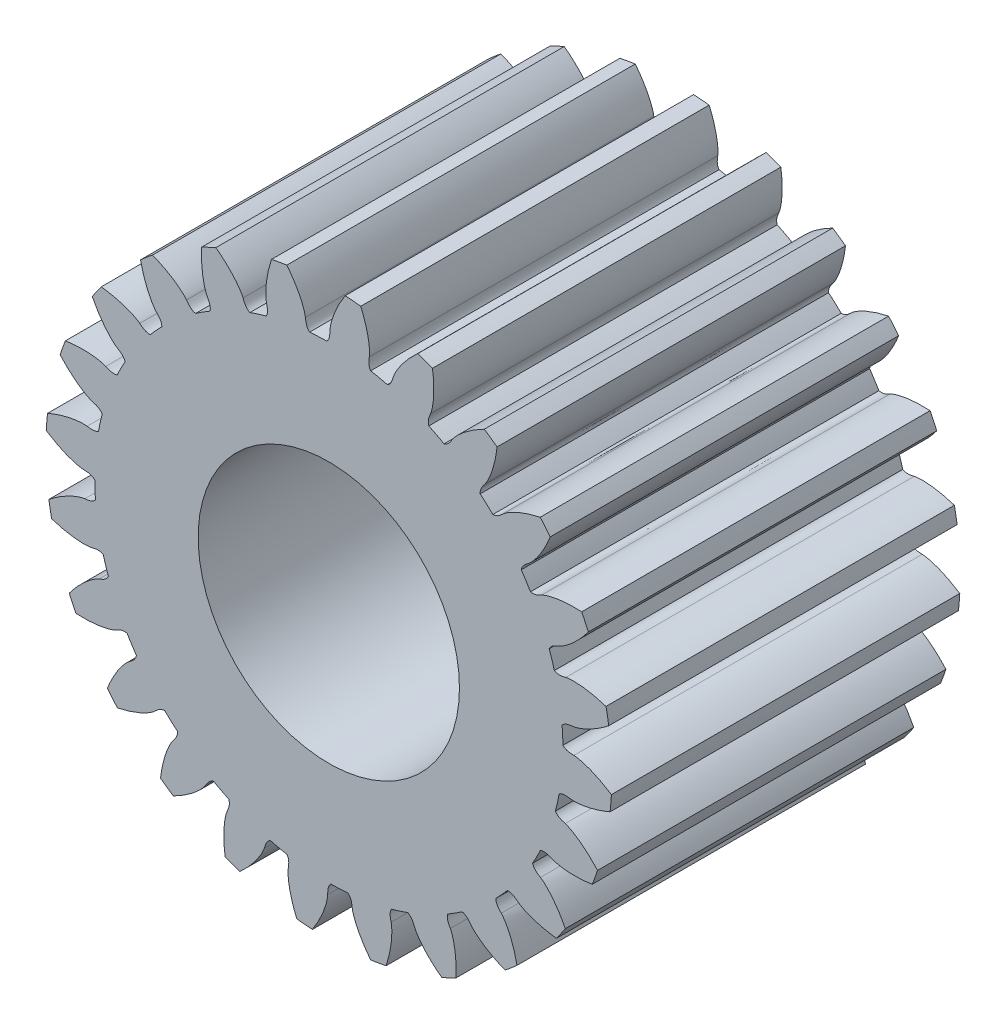
SolidWorks part; units mm, degrees
ref_plane "前视基准面" through (0, 0, 0) normal (0, 0, 1) x (1, 0, 0)
ref_plane "上视基准面" through (0, 0, 0) normal (0, 1, 0) x (1, 0, 0)
ref_plane "右视基准面" through (0, 0, 0) normal (1, 0, 0) x (0, 0, -1)
other "Configuration Table"
sketch "草图1" plane through (0, 0, 0) normal (0, 0, 1) x (1, 0, 0)
  line L0 (0, 0) -> (0.12, 5.9988) construction
  line L1 (0, 0) -> (0.5548, 6.4763) construction
  line L2 (0, 0) -> (1.3953, 6.3485) construction
  circle A0 centre (0, 0) radius 5.375
  circle A2 centre (0, 0) radius 6.5
  circle A3 centre (0, 0) radius 6
  spline S0 degree 4 poles (0.0267, 5.6277) (0.0268, 5.6323) (0.0274, 5.6451) (0.0298, 5.6692) (0.0354, 5.7085) (0.0451, 5.7581) (0.0606, 5.8218) (0.0826, 5.8959) (0.1105, 5.9764) (0.1451, 6.0628) (0.1832, 6.1477) (0.2244, 6.2312) (0.2685, 6.3131) (0.3253, 6.4109) (0.398, 6.5258) (0.4898, 6.6567) (0.6016, 6.8007) (0.7236, 6.9423) (0.85, 7.0774) (0.9849, 7.2085) (1.1204, 7.3315) (1.268, 7.4534) (1.4077, 7.5629) (1.5714, 7.6786) (1.7056, 7.77) (1.8898, 7.8829) (2.0007, 7.9473) (2.1328, 8.0198) (2.1927, 8.0506) (2.2296, 8.0696) knots 0 0 0 0 0 0.005377 0.015084 0.028532 0.04661 0.064855 0.092111 0.119476 0.146842 0.174209 0.201575 0.228941 0.256307 0.307035 0.361767 0.4165 0.471232 0.525964 0.580697 0.635429 0.690161 0.744894 0.799626 0.854358 0.909091 0.954545 1 1 1 1 1 construction
  spline S1 degree 4 poles (0.0267, 5.6277) (0.0268, 5.6323) (0.0274, 5.6451) (0.0298, 5.6692) (0.0354, 5.7085) (0.0451, 5.7581) (0.0606, 5.8218) (0.0826, 5.8959) (0.1105, 5.9764) (0.1451, 6.0628) (0.1832, 6.1477) (0.2244, 6.2312) (0.2685, 6.3131) (0.3119, 6.3879) (0.3451, 6.4416) (0.3666, 6.4752) (0.3757, 6.4891) knots 0 0 0 0 0 0.005377 0.015084 0.028532 0.04661 0.064855 0.092111 0.119476 0.146842 0.174209 0.201575 0.228941 0.256307 0.275859 0.275859 0.275859 0.275859 0.275859
  spline S2 degree 3 poles (0.0267, 5.6277) (0.0247, 5.5363) (0.0211, 5.4458) (-0.0474, 5.3748) knots 0 0 0 0 1 1 1 1
  spline S3 degree 3 poles (0.9308, 5.5502) (0.9172, 5.4599) (0.9054, 5.37) (0.9608, 5.2884) knots 0 0 0 0 1 1 1 1
  spline S4 degree 4 poles (0.9308, 5.5502) (0.9314, 5.5548) (0.933, 5.5675) (0.9348, 5.5917) (0.9359, 5.6313) (0.9348, 5.6819) (0.9304, 5.7473) (0.9214, 5.8241) (0.9075, 5.9082) (0.8881, 5.9991) (0.8651, 6.0893) (0.8386, 6.1786) (0.8091, 6.2668) (0.779, 6.3479) (0.7555, 6.4065) (0.74, 6.4432) (0.7334, 6.4585) knots 0 0 0 0 0 0.005377 0.015084 0.028532 0.04661 0.064855 0.092111 0.119476 0.146842 0.174209 0.201575 0.228941 0.256307 0.275859 0.275859 0.275859 0.275859 0.275859
  spline S5 degree 4 poles (1.4824, 5.429) (1.4837, 5.4334) (1.4876, 5.4456) (1.4961, 5.4683) (1.5117, 5.5048) (1.5339, 5.5502) (1.5653, 5.6077) (1.6057, 5.6737) (1.6536, 5.7442) (1.7093, 5.8187) (1.7681, 5.8908) (1.8295, 5.9608) (1.8933, 6.0285) (1.9546, 6.0895) (2.0005, 6.1328) (2.03, 6.1597) (2.0424, 6.1708) knots 0 0 0 0 0 0.005377 0.015084 0.028532 0.04661 0.064855 0.092111 0.119476 0.146842 0.174209 0.201575 0.228941 0.256307 0.275859 0.275859 0.275859 0.275859 0.275859
  spline S6 degree 3 poles (1.4824, 5.429) (1.4568, 5.3413) (1.4299, 5.2548) (1.3453, 5.2039) knots 0 0 0 0 1 1 1 1
  dimension "D1" = 12
  dimension "D2" = 13
  dimension "D3" = 10.75
  dimension "D5" = 3.75
  dimension "D6" = 11.25
sketch "草图3" plane through (0, 0, 0) normal (0, 0, 1) x (1, 0, 0)
  circle A0 centre (0, 0) radius 5.375 construction
  circle A1 centre (0, 0) radius 6.5 construction
  arc A2 (1.3453, 5.2039) -> (0.9608, 5.2884) centre (0, 0) ccw
  arc A3 (0.7334, 6.4585) -> (0.3757, 6.4891) centre (0, 0) ccw
  arc A4 (2.38, 6.0486) -> (2.0424, 6.1708) centre (0, 0) ccw
  arc A5 (2.6463, 4.6784) -> (2.2968, 4.8595) centre (0, 0) ccw
  arc A6 (3.8644, 5.2265) -> (3.5699, 5.4319) centre (0, 0) ccw
  arc A7 (3.767, 3.8341) -> (3.4763, 4.0995) centre (0, 0) ccw
  arc A8 (5.0854, 4.0482) -> (4.8542, 4.3229) centre (0, 0) ccw
  arc A9 (4.631, 2.7285) -> (4.4189, 3.0601) centre (0, 0) ccw
  arc A10 (5.9599, 2.5941) -> (5.8076, 2.9192) centre (0, 0) ccw
  arc A11 (5.1794, 1.4369) -> (5.0603, 1.8121) centre (0, 0) ccw
  arc A12 (6.4282, 0.9632) -> (6.3653, 1.3166) centre (0, 0) ccw
  arc A13 (5.3748, 0.0474) -> (5.3569, 0.4407) centre (0, 0) ccw
  arc A14 (6.4585, -0.7334) -> (6.4891, -0.3757) centre (0, 0) ccw
  arc A15 (5.2039, -1.3453) -> (5.2884, -0.9608) centre (0, 0) ccw
  arc A16 (6.0486, -2.38) -> (6.1708, -2.0424) centre (0, 0) ccw
  arc A17 (4.6784, -2.6463) -> (4.8595, -2.2968) centre (0, 0) ccw
  arc A18 (5.2265, -3.8644) -> (5.4319, -3.5699) centre (0, 0) ccw
  arc A19 (3.8341, -3.767) -> (4.0995, -3.4763) centre (0, 0) ccw
  arc A20 (4.0482, -5.0854) -> (4.3229, -4.8542) centre (0, 0) ccw
  arc A21 (2.7285, -4.631) -> (3.0601, -4.4189) centre (0, 0) ccw
  arc A22 (2.5941, -5.9599) -> (2.9192, -5.8076) centre (0, 0) ccw
  arc A23 (1.4369, -5.1794) -> (1.8121, -5.0603) centre (0, 0) ccw
  arc A24 (0.9632, -6.4282) -> (1.3166, -6.3653) centre (0, 0) ccw
  arc A25 (0.0474, -5.3748) -> (0.4407, -5.3569) centre (0, 0) ccw
  arc A26 (-0.7334, -6.4585) -> (-0.3757, -6.4891) centre (0, 0) ccw
  arc A27 (-1.3453, -5.2039) -> (-0.9608, -5.2884) centre (0, 0) ccw
  arc A28 (-2.38, -6.0486) -> (-2.0424, -6.1708) centre (0, 0) ccw
  arc A29 (-2.6463, -4.6784) -> (-2.2968, -4.8595) centre (0, 0) ccw
  arc A30 (-3.8644, -5.2265) -> (-3.5699, -5.4319) centre (0, 0) ccw
  arc A31 (-3.767, -3.8341) -> (-3.4763, -4.0995) centre (0, 0) ccw
  arc A32 (-5.0854, -4.0482) -> (-4.8542, -4.3229) centre (0, 0) ccw
  arc A33 (-4.631, -2.7285) -> (-4.4189, -3.0601) centre (0, 0) ccw
  arc A34 (-5.9599, -2.5941) -> (-5.8076, -2.9192) centre (0, 0) ccw
  arc A35 (-5.1794, -1.4369) -> (-5.0603, -1.8121) centre (0, 0) ccw
  arc A36 (-6.4282, -0.9632) -> (-6.3653, -1.3166) centre (0, 0) ccw
  arc A37 (-5.3748, -0.0474) -> (-5.3569, -0.4407) centre (0, 0) ccw
  arc A38 (-6.4585, 0.7334) -> (-6.4891, 0.3757) centre (0, 0) ccw
  arc A39 (-5.2039, 1.3453) -> (-5.2884, 0.9608) centre (0, 0) ccw
  arc A40 (-6.0486, 2.38) -> (-6.1708, 2.0424) centre (0, 0) ccw
  arc A41 (-4.6784, 2.6463) -> (-4.8595, 2.2968) centre (0, 0) ccw
  arc A42 (-5.2265, 3.8644) -> (-5.4319, 3.5699) centre (0, 0) ccw
  arc A43 (-3.8341, 3.767) -> (-4.0995, 3.4763) centre (0, 0) ccw
  arc A44 (-4.0482, 5.0854) -> (-4.3229, 4.8542) centre (0, 0) ccw
  arc A45 (-2.7285, 4.631) -> (-3.0601, 4.4189) centre (0, 0) ccw
  arc A46 (-2.5941, 5.9599) -> (-2.9192, 5.8076) centre (0, 0) ccw
  arc A47 (-1.4369, 5.1794) -> (-1.8121, 5.0603) centre (0, 0) ccw
  arc A48 (-0.9632, 6.4282) -> (-1.3166, 6.3653) centre (0, 0) ccw
  arc A49 (-0.0474, 5.3748) -> (-0.4407, 5.3569) centre (0, 0) ccw
  spline S2 degree 3 poles (-2979.464, -335.7938) (2983.1764, 360.5593) (-2981.2233, -350.1939) (2981.0593, 349.1567) knots -35.7145 -35.7145 -35.7145 -35.7145 35.661939 35.661939 35.661939 35.661939 only from (0.9308, 5.5502) to (0.9608, 5.2884) construction
  spline S3 degree 4 poles (-2958.437, 495.2525) (-31.7135, 9.2993) (0.2826, 4.478) (0.9188, 5.0343) (0.9359, 5.6313) (0.9348, 5.6819) (0.9304, 5.7473) (0.9214, 5.8241) (0.9075, 5.9082) (0.8881, 5.9991) (0.8651, 6.0893) (0.8386, 6.1786) (0.8091, 6.2668) (-0.2975, 9.2485) (-5.2665, 10.4853) (-15.9567, 23.5893) (2233.9266, -1996.6934) knots -0.655787 -0.655787 -0.655787 -0.655787 -0.655787 0.005377 0.015084 0.028532 0.04661 0.064855 0.092111 0.119476 0.146842 0.174209 0.201575 0.228941 0.256307 3.912064 3.912064 3.912064 3.912064 3.912064 only from (0.9308, 5.5502) to (0.7334, 6.4585) construction
  spline S4 degree 3 poles (2878.9491, -837.6248) (-2878.3956, 862.6608) (2878.2338, -852.1143) (-2878.2485, 851.0643) knots -35.7145 -35.7145 -35.7145 -35.7145 35.661939 35.661939 35.661939 35.661939 only from (0.0267, 5.6277) to (-0.0474, 5.3748) construction
  spline S5 degree 4 poles (2999.5664, -15.1095) (32.833, 3.7702) (0.4831, 4.4609) (-0.0492, 5.1172) (0.0354, 5.7085) (0.0451, 5.7581) (0.0606, 5.8218) (0.0826, 5.8959) (0.1105, 5.9764) (0.1451, 6.0628) (0.1832, 6.1477) (0.2244, 6.2312) (0.2685, 6.3131) (1.8661, 9.0632) (6.973, 9.4369) (19.7362, 20.5319) (-2540.9637, -1587.677) knots -0.655787 -0.655787 -0.655787 -0.655787 -0.655787 0.005377 0.015084 0.028532 0.04661 0.064855 0.092111 0.119476 0.146842 0.174209 0.201575 0.228941 0.256307 3.912064 3.912064 3.912064 3.912064 3.912064 only from (0.0267, 5.6277) to (0.3757, 6.4891) construction
  spline S6 degree 4 poles (1.4824, 5.429) (1.4837, 5.4334) (1.4876, 5.4456) (1.4961, 5.4683) (1.5117, 5.5048) (1.5339, 5.5502) (1.5653, 5.6077) (1.6057, 5.6737) (1.6536, 5.7442) (1.7093, 5.8187) (1.7681, 5.8908) (1.8295, 5.9608) (1.8933, 6.0285) (1.9546, 6.0895) (2.0005, 6.1328) (2.03, 6.1597) (2.0424, 6.1708) knots 0 0 0 0 0 0.005377 0.015084 0.028532 0.04661 0.064855 0.092111 0.119476 0.146842 0.174209 0.201575 0.228941 0.256307 0.275859 0.275859 0.275859 0.275859 0.275859
  spline S7 degree 3 poles (1.4824, 5.429) (1.4568, 5.3413) (1.4299, 5.2548) (1.3453, 5.2039) knots 0 0 0 0 1 1 1 1
  spline S8 degree 3 poles (0.9308, 5.5502) (0.9172, 5.4599) (0.9054, 5.37) (0.9608, 5.2884) knots 0 0 0 0 1 1 1 1
  spline S9 degree 4 poles (0.9308, 5.5502) (0.9314, 5.5548) (0.933, 5.5675) (0.9348, 5.5917) (0.9359, 5.6313) (0.9348, 5.6819) (0.9304, 5.7473) (0.9214, 5.8241) (0.9075, 5.9082) (0.8881, 5.9991) (0.8651, 6.0893) (0.8386, 6.1786) (0.8091, 6.2668) (0.779, 6.3479) (0.7555, 6.4065) (0.74, 6.4432) (0.7334, 6.4585) knots 0 0 0 0 0 0.005377 0.015084 0.028532 0.04661 0.064855 0.092111 0.119476 0.146842 0.174209 0.201575 0.228941 0.256307 0.275859 0.275859 0.275859 0.275859 0.275859
  spline S10 degree 3 poles (0.0267, 5.6277) (0.0247, 5.5363) (0.0211, 5.4458) (-0.0474, 5.3748) knots 0 0 0 0 1 1 1 1
  spline S11 degree 4 poles (0.0267, 5.6277) (0.0268, 5.6323) (0.0274, 5.6451) (0.0298, 5.6692) (0.0354, 5.7085) (0.0451, 5.7581) (0.0606, 5.8218) (0.0826, 5.8959) (0.1105, 5.9764) (0.1451, 6.0628) (0.1832, 6.1477) (0.2244, 6.2312) (0.2685, 6.3131) (0.3119, 6.3879) (0.3451, 6.4416) (0.3666, 6.4752) (0.3757, 6.4891) knots 0 0 0 0 0 0.005377 0.015084 0.028532 0.04661 0.064855 0.092111 0.119476 0.146842 0.174209 0.201575 0.228941 0.256307 0.275859 0.275859 0.275859 0.275859 0.275859
  spline S12 degree 3 poles (2.3356, 5.1202) (2.2991, 5.0365) (2.2644, 4.9527) (2.2968, 4.8595) knots 0 0 0 0 1 1 1 1
  spline S13 degree 4 poles (2.3356, 5.1202) (2.3374, 5.1244) (2.3422, 5.1363) (2.3502, 5.1592) (2.3615, 5.1972) (2.3735, 5.2463) (2.3862, 5.3106) (2.3974, 5.3872) (2.4057, 5.472) (2.4106, 5.5649) (2.4116, 5.6579) (2.4091, 5.751) (2.4035, 5.8439) (2.3954, 5.93) (2.3879, 5.9926) (2.3824, 6.0322) (2.38, 6.0486) knots 0 0 0 0 0 0.005377 0.015084 0.028532 0.04661 0.064855 0.092111 0.119476 0.146842 0.174209 0.201575 0.228941 0.256307 0.275859 0.275859 0.275859 0.275859 0.275859
  spline S14 degree 4 poles (2.837, 4.8603) (2.8394, 4.8643) (2.8463, 4.8751) (2.8604, 4.8948) (2.8849, 4.926) (2.9181, 4.9641) (2.9634, 5.0115) (3.0195, 5.0647) (3.084, 5.1205) (3.1571, 5.178) (3.2325, 5.2325) (3.31, 5.2842) (3.3891, 5.3331) (3.4641, 5.3761) (3.5197, 5.4061) (3.5551, 5.4244) (3.5699, 5.4319) knots 0 0 0 0 0 0.005377 0.015084 0.028532 0.04661 0.064855 0.092111 0.119476 0.146842 0.174209 0.201575 0.228941 0.256307 0.275859 0.275859 0.275859 0.275859 0.275859
  spline S15 degree 3 poles (2.837, 4.8603) (2.7896, 4.7823) (2.7412, 4.7056) (2.6463, 4.6784) knots 0 0 0 0 1 1 1 1
  spline S16 degree 3 poles (3.5812, 4.3413) (3.5243, 4.2698) (3.4691, 4.1979) (3.4763, 4.0995) knots 0 0 0 0 1 1 1 1
  spline S17 degree 4 poles (3.5812, 4.3413) (3.584, 4.3449) (3.5918, 4.3551) (3.6054, 4.3752) (3.6262, 4.4089) (3.6505, 4.4533) (3.6794, 4.5121) (3.71, 4.5831) (3.74, 4.6629) (3.7687, 4.7514) (3.7938, 4.841) (3.8155, 4.9315) (3.8341, 5.0227) (3.8486, 5.1079) (3.8575, 5.1704) (3.8625, 5.21) (3.8644, 5.2265) knots 0 0 0 0 0 0.005377 0.015084 0.028532 0.04661 0.064855 0.092111 0.119476 0.146842 0.174209 0.201575 0.228941 0.256307 0.275859 0.275859 0.275859 0.275859 0.275859
  spline S18 degree 4 poles (3.9983, 3.9605) (4.0016, 3.9636) (4.0111, 3.9723) (4.0298, 3.9877) (4.0615, 4.0114) (4.1035, 4.0397) (4.1595, 4.0737) (4.2274, 4.1107) (4.3042, 4.1478) (4.3896, 4.1844) (4.4766, 4.2176) (4.5648, 4.2474) (4.6539, 4.2742) (4.7375, 4.2964) (4.7989, 4.3109) (4.8379, 4.3194) (4.8542, 4.3229) knots 0 0 0 0 0 0.005377 0.015084 0.028532 0.04661 0.064855 0.092111 0.119476 0.146842 0.174209 0.201575 0.228941 0.256307 0.275859 0.275859 0.275859 0.275859 0.275859
  spline S19 degree 3 poles (3.9983, 3.9605) (3.9323, 3.8973) (3.8657, 3.8358) (3.767, 3.8341) knots 0 0 0 0 1 1 1 1
  spline S20 degree 3 poles (4.5828, 3.2665) (4.5093, 3.2122) (4.4374, 3.157) (4.4189, 3.0601) knots 0 0 0 0 1 1 1 1
  spline S21 degree 4 poles (4.5828, 3.2665) (4.5864, 3.2692) (4.5966, 3.2771) (4.6149, 3.2929) (4.6438, 3.3201) (4.6787, 3.3567) (4.7218, 3.406) (4.7698, 3.4667) (4.8194, 3.536) (4.87, 3.614) (4.9175, 3.6941) (4.9619, 3.7759) (5.0034, 3.8592) (5.0395, 3.9378) (5.0643, 3.9959) (5.0793, 4.0328) (5.0854, 4.0482) knots 0 0 0 0 0 0.005377 0.015084 0.028532 0.04661 0.064855 0.092111 0.119476 0.146842 0.174209 0.201575 0.228941 0.256307 0.275859 0.275859 0.275859 0.275859 0.275859
  spline S22 degree 4 poles (4.8871, 2.7907) (4.8911, 2.7929) (4.9025, 2.7988) (4.9246, 2.8088) (4.9614, 2.8236) (5.0092, 2.84) (5.0721, 2.8584) (5.1473, 2.8765) (5.231, 2.8925) (5.3231, 2.9057) (5.4157, 2.9152) (5.5086, 2.9212) (5.6016, 2.9241) (5.6881, 2.9238) (5.7512, 2.922) (5.791, 2.9201) (5.8076, 2.9192) knots 0 0 0 0 0 0.005377 0.015084 0.028532 0.04661 0.064855 0.092111 0.119476 0.146842 0.174209 0.201575 0.228941 0.256307 0.275859 0.275859 0.275859 0.275859 0.275859
  spline S23 degree 3 poles (4.8871, 2.7907) (4.807, 2.7468) (4.7267, 2.7046) (4.631, 2.7285) knots 0 0 0 0 1 1 1 1
  spline S24 degree 3 poles (5.272, 1.9691) (5.187, 1.9356) (5.1033, 1.9009) (5.0603, 1.8121) knots 0 0 0 0 1 1 1 1
  spline S25 degree 4 poles (5.272, 1.9691) (5.2763, 1.9707) (5.2881, 1.9757) (5.31, 1.9863) (5.3448, 2.0051) (5.3881, 2.0314) (5.4425, 2.0679) (5.5045, 2.1141) (5.5704, 2.1682) (5.6395, 2.2304) (5.706, 2.2955) (5.7701, 2.3631) (5.8318, 2.4327) (5.887, 2.4993) (5.9259, 2.549) (5.95, 2.5808) (5.9599, 2.5941) knots 0 0 0 0 0 0.005377 0.015084 0.028532 0.04661 0.064855 0.092111 0.119476 0.146842 0.174209 0.201575 0.228941 0.256307 0.275859 0.275859 0.275859 0.275859 0.275859
  spline S26 degree 4 poles (5.4428, 1.4307) (5.4473, 1.4318) (5.4598, 1.4345) (5.4838, 1.4385) (5.5231, 1.4432) (5.5736, 1.4467) (5.6391, 1.4482) (5.7164, 1.4462) (5.8014, 1.44) (5.8938, 1.429) (5.9857, 1.4142) (6.077, 1.396) (6.1675, 1.3746) (6.251, 1.352) (6.3115, 1.3339) (6.3495, 1.3218) (6.3653, 1.3166) knots 0 0 0 0 0 0.005377 0.015084 0.028532 0.04661 0.064855 0.092111 0.119476 0.146842 0.174209 0.201575 0.228941 0.256307 0.275859 0.275859 0.275859 0.275859 0.275859
  spline S27 degree 3 poles (5.4428, 1.4307) (5.3541, 1.409) (5.2657, 1.3891) (5.1794, 1.4369) knots 0 0 0 0 1 1 1 1
  spline S28 degree 3 poles (5.602, 0.5375) (5.5112, 0.5272) (5.4214, 0.5153) (5.3569, 0.4407) knots 0 0 0 0 1 1 1 1
  spline S29 degree 4 poles (5.602, 0.5375) (5.6066, 0.538) (5.6193, 0.5397) (5.6431, 0.5443) (5.6817, 0.5534) (5.7302, 0.5676) (5.7922, 0.5888) (5.8641, 0.6174) (5.9417, 0.6526) (6.0246, 0.6948) (6.1057, 0.7404) (6.1851, 0.7891) (6.2627, 0.8404) (6.3332, 0.8905) (6.3837, 0.9284) (6.4152, 0.9529) (6.4282, 0.9632) knots 0 0 0 0 0 0.005377 0.015084 0.028532 0.04661 0.064855 0.092111 0.119476 0.146842 0.174209 0.201575 0.228941 0.256307 0.275859 0.275859 0.275859 0.275859 0.275859
  spline S30 degree 4 poles (5.6277, -0.0267) (5.6323, -0.0268) (5.6451, -0.0274) (5.6692, -0.0298) (5.7085, -0.0354) (5.7581, -0.0451) (5.8218, -0.0606) (5.8959, -0.0826) (5.9764, -0.1105) (6.0628, -0.1451) (6.1477, -0.1832) (6.2312, -0.2244) (6.3131, -0.2685) (6.3879, -0.3119) (6.4416, -0.3451) (6.4752, -0.3666) (6.4891, -0.3757) knots 0 0 0 0 0 0.005377 0.015084 0.028532 0.04661 0.064855 0.092111 0.119476 0.146842 0.174209 0.201575 0.228941 0.256307 0.275859 0.275859 0.275859 0.275859 0.275859
  spline S31 degree 3 poles (5.6277, -0.0267) (5.5363, -0.0247) (5.4458, -0.0211) (5.3748, 0.0474) knots 0 0 0 0 1 1 1 1
  spline S32 degree 3 poles (5.5502, -0.9308) (5.4599, -0.9172) (5.37, -0.9054) (5.2884, -0.9608) knots 0 0 0 0 1 1 1 1
  spline S33 degree 4 poles (5.5502, -0.9308) (5.5548, -0.9314) (5.5675, -0.933) (5.5917, -0.9348) (5.6313, -0.9359) (5.6819, -0.9348) (5.7473, -0.9304) (5.8241, -0.9214) (5.9082, -0.9075) (5.9991, -0.8881) (6.0893, -0.8651) (6.1786, -0.8386) (6.2668, -0.8091) (6.3479, -0.779) (6.4065, -0.7555) (6.4432, -0.74) (6.4585, -0.7334) knots 0 0 0 0 0 0.005377 0.015084 0.028532 0.04661 0.064855 0.092111 0.119476 0.146842 0.174209 0.201575 0.228941 0.256307 0.275859 0.275859 0.275859 0.275859 0.275859
  spline S34 degree 4 poles (5.429, -1.4824) (5.4334, -1.4837) (5.4456, -1.4876) (5.4683, -1.4961) (5.5048, -1.5117) (5.5502, -1.5339) (5.6077, -1.5653) (5.6737, -1.6057) (5.7442, -1.6536) (5.8187, -1.7093) (5.8908, -1.7681) (5.9608, -1.8295) (6.0285, -1.8933) (6.0895, -1.9546) (6.1328, -2.0005) (6.1597, -2.03) (6.1708, -2.0424) knots 0 0 0 0 0 0.005377 0.015084 0.028532 0.04661 0.064855 0.092111 0.119476 0.146842 0.174209 0.201575 0.228941 0.256307 0.275859 0.275859 0.275859 0.275859 0.275859
  spline S35 degree 3 poles (5.429, -1.4824) (5.3413, -1.4568) (5.2548, -1.4299) (5.2039, -1.3453) knots 0 0 0 0 1 1 1 1
  spline S36 degree 3 poles (5.1202, -2.3356) (5.0365, -2.2991) (4.9527, -2.2644) (4.8595, -2.2968) knots 0 0 0 0 1 1 1 1
  spline S37 degree 4 poles (5.1202, -2.3356) (5.1244, -2.3374) (5.1363, -2.3422) (5.1592, -2.3502) (5.1972, -2.3615) (5.2463, -2.3735) (5.3106, -2.3862) (5.3872, -2.3974) (5.472, -2.4057) (5.5649, -2.4106) (5.6579, -2.4116) (5.751, -2.4091) (5.8439, -2.4035) (5.93, -2.3954) (5.9926, -2.3879) (6.0322, -2.3824) (6.0486, -2.38) knots 0 0 0 0 0 0.005377 0.015084 0.028532 0.04661 0.064855 0.092111 0.119476 0.146842 0.174209 0.201575 0.228941 0.256307 0.275859 0.275859 0.275859 0.275859 0.275859
  spline S38 degree 4 poles (4.8603, -2.837) (4.8643, -2.8394) (4.8751, -2.8463) (4.8948, -2.8604) (4.926, -2.8849) (4.9641, -2.9181) (5.0115, -2.9634) (5.0647, -3.0195) (5.1205, -3.084) (5.178, -3.1571) (5.2325, -3.2325) (5.2842, -3.31) (5.3331, -3.3891) (5.3761, -3.4641) (5.4061, -3.5197) (5.4244, -3.5551) (5.4319, -3.5699) knots 0 0 0 0 0 0.005377 0.015084 0.028532 0.04661 0.064855 0.092111 0.119476 0.146842 0.174209 0.201575 0.228941 0.256307 0.275859 0.275859 0.275859 0.275859 0.275859
  spline S39 degree 3 poles (4.8603, -2.837) (4.7823, -2.7896) (4.7056, -2.7412) (4.6784, -2.6463) knots 0 0 0 0 1 1 1 1
  spline S40 degree 3 poles (4.3413, -3.5812) (4.2698, -3.5243) (4.1979, -3.4691) (4.0995, -3.4763) knots 0 0 0 0 1 1 1 1
  spline S41 degree 4 poles (4.3413, -3.5812) (4.3449, -3.584) (4.3551, -3.5918) (4.3752, -3.6054) (4.4089, -3.6262) (4.4533, -3.6505) (4.5121, -3.6794) (4.5831, -3.71) (4.6629, -3.74) (4.7514, -3.7687) (4.841, -3.7938) (4.9315, -3.8155) (5.0227, -3.8341) (5.1079, -3.8486) (5.1704, -3.8575) (5.21, -3.8625) (5.2265, -3.8644) knots 0 0 0 0 0 0.005377 0.015084 0.028532 0.04661 0.064855 0.092111 0.119476 0.146842 0.174209 0.201575 0.228941 0.256307 0.275859 0.275859 0.275859 0.275859 0.275859
  spline S42 degree 4 poles (3.9605, -3.9983) (3.9636, -4.0016) (3.9723, -4.0111) (3.9877, -4.0298) (4.0114, -4.0615) (4.0397, -4.1035) (4.0737, -4.1595) (4.1107, -4.2274) (4.1478, -4.3042) (4.1844, -4.3896) (4.2176, -4.4766) (4.2474, -4.5648) (4.2742, -4.6539) (4.2964, -4.7375) (4.3109, -4.7989) (4.3194, -4.8379) (4.3229, -4.8542) knots 0 0 0 0 0 0.005377 0.015084 0.028532 0.04661 0.064855 0.092111 0.119476 0.146842 0.174209 0.201575 0.228941 0.256307 0.275859 0.275859 0.275859 0.275859 0.275859
  spline S43 degree 3 poles (3.9605, -3.9983) (3.8973, -3.9323) (3.8358, -3.8657) (3.8341, -3.767) knots 0 0 0 0 1 1 1 1
  spline S44 degree 3 poles (3.2665, -4.5828) (3.2122, -4.5093) (3.157, -4.4374) (3.0601, -4.4189) knots 0 0 0 0 1 1 1 1
  spline S45 degree 4 poles (3.2665, -4.5828) (3.2692, -4.5864) (3.2771, -4.5966) (3.2929, -4.6149) (3.3201, -4.6438) (3.3567, -4.6787) (3.406, -4.7218) (3.4667, -4.7698) (3.536, -4.8194) (3.614, -4.87) (3.6941, -4.9175) (3.7759, -4.9619) (3.8592, -5.0034) (3.9378, -5.0395) (3.9959, -5.0643) (4.0328, -5.0793) (4.0482, -5.0854) knots 0 0 0 0 0 0.005377 0.015084 0.028532 0.04661 0.064855 0.092111 0.119476 0.146842 0.174209 0.201575 0.228941 0.256307 0.275859 0.275859 0.275859 0.275859 0.275859
  spline S46 degree 4 poles (2.7907, -4.8871) (2.7929, -4.8911) (2.7988, -4.9025) (2.8088, -4.9246) (2.8236, -4.9614) (2.84, -5.0092) (2.8584, -5.0721) (2.8765, -5.1473) (2.8925, -5.231) (2.9057, -5.3231) (2.9152, -5.4157) (2.9212, -5.5086) (2.9241, -5.6016) (2.9238, -5.6881) (2.922, -5.7512) (2.9201, -5.791) (2.9192, -5.8076) knots 0 0 0 0 0 0.005377 0.015084 0.028532 0.04661 0.064855 0.092111 0.119476 0.146842 0.174209 0.201575 0.228941 0.256307 0.275859 0.275859 0.275859 0.275859 0.275859
  spline S47 degree 3 poles (2.7907, -4.8871) (2.7468, -4.807) (2.7046, -4.7267) (2.7285, -4.631) knots 0 0 0 0 1 1 1 1
  spline S48 degree 3 poles (1.9691, -5.272) (1.9356, -5.187) (1.9009, -5.1033) (1.8121, -5.0603) knots 0 0 0 0 1 1 1 1
  spline S49 degree 4 poles (1.9691, -5.272) (1.9707, -5.2763) (1.9757, -5.2881) (1.9863, -5.31) (2.0051, -5.3448) (2.0314, -5.3881) (2.0679, -5.4425) (2.1141, -5.5045) (2.1682, -5.5704) (2.2304, -5.6395) (2.2955, -5.706) (2.3631, -5.7701) (2.4327, -5.8318) (2.4993, -5.887) (2.549, -5.9259) (2.5808, -5.95) (2.5941, -5.9599) knots 0 0 0 0 0 0.005377 0.015084 0.028532 0.04661 0.064855 0.092111 0.119476 0.146842 0.174209 0.201575 0.228941 0.256307 0.275859 0.275859 0.275859 0.275859 0.275859
  spline S50 degree 4 poles (1.4307, -5.4428) (1.4318, -5.4473) (1.4345, -5.4598) (1.4385, -5.4838) (1.4432, -5.5231) (1.4467, -5.5736) (1.4482, -5.6391) (1.4462, -5.7164) (1.44, -5.8014) (1.429, -5.8938) (1.4142, -5.9857) (1.396, -6.077) (1.3746, -6.1675) (1.352, -6.251) (1.3339, -6.3115) (1.3218, -6.3495) (1.3166, -6.3653) knots 0 0 0 0 0 0.005377 0.015084 0.028532 0.04661 0.064855 0.092111 0.119476 0.146842 0.174209 0.201575 0.228941 0.256307 0.275859 0.275859 0.275859 0.275859 0.275859
  spline S51 degree 3 poles (1.4307, -5.4428) (1.409, -5.3541) (1.3891, -5.2657) (1.4369, -5.1794) knots 0 0 0 0 1 1 1 1
  spline S52 degree 3 poles (0.5375, -5.602) (0.5272, -5.5112) (0.5153, -5.4214) (0.4407, -5.3569) knots 0 0 0 0 1 1 1 1
  spline S53 degree 4 poles (0.5375, -5.602) (0.538, -5.6066) (0.5397, -5.6193) (0.5443, -5.6431) (0.5534, -5.6817) (0.5676, -5.7302) (0.5888, -5.7922) (0.6174, -5.8641) (0.6526, -5.9417) (0.6948, -6.0246) (0.7404, -6.1057) (0.7891, -6.1851) (0.8404, -6.2627) (0.8905, -6.3332) (0.9284, -6.3837) (0.9529, -6.4152) (0.9632, -6.4282) knots 0 0 0 0 0 0.005377 0.015084 0.028532 0.04661 0.064855 0.092111 0.119476 0.146842 0.174209 0.201575 0.228941 0.256307 0.275859 0.275859 0.275859 0.275859 0.275859
  spline S54 degree 4 poles (-0.0267, -5.6277) (-0.0268, -5.6323) (-0.0274, -5.6451) (-0.0298, -5.6692) (-0.0354, -5.7085) (-0.0451, -5.7581) (-0.0606, -5.8218) (-0.0826, -5.8959) (-0.1105, -5.9764) (-0.1451, -6.0628) (-0.1832, -6.1477) (-0.2244, -6.2312) (-0.2685, -6.3131) (-0.3119, -6.3879) (-0.3451, -6.4416) (-0.3666, -6.4752) (-0.3757, -6.4891) knots 0 0 0 0 0 0.005377 0.015084 0.028532 0.04661 0.064855 0.092111 0.119476 0.146842 0.174209 0.201575 0.228941 0.256307 0.275859 0.275859 0.275859 0.275859 0.275859
  spline S55 degree 3 poles (-0.0267, -5.6277) (-0.0247, -5.5363) (-0.0211, -5.4458) (0.0474, -5.3748) knots 0 0 0 0 1 1 1 1
  spline S56 degree 3 poles (-0.9308, -5.5502) (-0.9172, -5.4599) (-0.9054, -5.37) (-0.9608, -5.2884) knots 0 0 0 0 1 1 1 1
  spline S57 degree 4 poles (-0.9308, -5.5502) (-0.9314, -5.5548) (-0.933, -5.5675) (-0.9348, -5.5917) (-0.9359, -5.6313) (-0.9348, -5.6819) (-0.9304, -5.7473) (-0.9214, -5.8241) (-0.9075, -5.9082) (-0.8881, -5.9991) (-0.8651, -6.0893) (-0.8386, -6.1786) (-0.8091, -6.2668) (-0.779, -6.3479) (-0.7555, -6.4065) (-0.74, -6.4432) (-0.7334, -6.4585) knots 0 0 0 0 0 0.005377 0.015084 0.028532 0.04661 0.064855 0.092111 0.119476 0.146842 0.174209 0.201575 0.228941 0.256307 0.275859 0.275859 0.275859 0.275859 0.275859
  spline S58 degree 4 poles (-1.4824, -5.429) (-1.4837, -5.4334) (-1.4876, -5.4456) (-1.4961, -5.4683) (-1.5117, -5.5048) (-1.5339, -5.5502) (-1.5653, -5.6077) (-1.6057, -5.6737) (-1.6536, -5.7442) (-1.7093, -5.8187) (-1.7681, -5.8908) (-1.8295, -5.9608) (-1.8933, -6.0285) (-1.9546, -6.0895) (-2.0005, -6.1328) (-2.03, -6.1597) (-2.0424, -6.1708) knots 0 0 0 0 0 0.005377 0.015084 0.028532 0.04661 0.064855 0.092111 0.119476 0.146842 0.174209 0.201575 0.228941 0.256307 0.275859 0.275859 0.275859 0.275859 0.275859
  spline S59 degree 3 poles (-1.4824, -5.429) (-1.4568, -5.3413) (-1.4299, -5.2548) (-1.3453, -5.2039) knots 0 0 0 0 1 1 1 1
  spline S60 degree 3 poles (-2.3356, -5.1202) (-2.2991, -5.0365) (-2.2644, -4.9527) (-2.2968, -4.8595) knots 0 0 0 0 1 1 1 1
  spline S61 degree 4 poles (-2.3356, -5.1202) (-2.3374, -5.1244) (-2.3422, -5.1363) (-2.3502, -5.1592) (-2.3615, -5.1972) (-2.3735, -5.2463) (-2.3862, -5.3106) (-2.3974, -5.3872) (-2.4057, -5.472) (-2.4106, -5.5649) (-2.4116, -5.6579) (-2.4091, -5.751) (-2.4035, -5.8439) (-2.3954, -5.93) (-2.3879, -5.9926) (-2.3824, -6.0322) (-2.38, -6.0486) knots 0 0 0 0 0 0.005377 0.015084 0.028532 0.04661 0.064855 0.092111 0.119476 0.146842 0.174209 0.201575 0.228941 0.256307 0.275859 0.275859 0.275859 0.275859 0.275859
  spline S62 degree 4 poles (-2.837, -4.8603) (-2.8394, -4.8643) (-2.8463, -4.8751) (-2.8604, -4.8948) (-2.8849, -4.926) (-2.9181, -4.9641) (-2.9634, -5.0115) (-3.0195, -5.0647) (-3.084, -5.1205) (-3.1571, -5.178) (-3.2325, -5.2325) (-3.31, -5.2842) (-3.3891, -5.3331) (-3.4641, -5.3761) (-3.5197, -5.4061) (-3.5551, -5.4244) (-3.5699, -5.4319) knots 0 0 0 0 0 0.005377 0.015084 0.028532 0.04661 0.064855 0.092111 0.119476 0.146842 0.174209 0.201575 0.228941 0.256307 0.275859 0.275859 0.275859 0.275859 0.275859
  spline S63 degree 3 poles (-2.837, -4.8603) (-2.7896, -4.7823) (-2.7412, -4.7056) (-2.6463, -4.6784) knots 0 0 0 0 1 1 1 1
  spline S64 degree 3 poles (-3.5812, -4.3413) (-3.5243, -4.2698) (-3.4691, -4.1979) (-3.4763, -4.0995) knots 0 0 0 0 1 1 1 1
  spline S65 degree 4 poles (-3.5812, -4.3413) (-3.584, -4.3449) (-3.5918, -4.3551) (-3.6054, -4.3752) (-3.6262, -4.4089) (-3.6505, -4.4533) (-3.6794, -4.5121) (-3.71, -4.5831) (-3.74, -4.6629) (-3.7687, -4.7514) (-3.7938, -4.841) (-3.8155, -4.9315) (-3.8341, -5.0227) (-3.8486, -5.1079) (-3.8575, -5.1704) (-3.8625, -5.21) (-3.8644, -5.2265) knots 0 0 0 0 0 0.005377 0.015084 0.028532 0.04661 0.064855 0.092111 0.119476 0.146842 0.174209 0.201575 0.228941 0.256307 0.275859 0.275859 0.275859 0.275859 0.275859
  spline S66 degree 4 poles (-3.9983, -3.9605) (-4.0016, -3.9636) (-4.0111, -3.9723) (-4.0298, -3.9877) (-4.0615, -4.0114) (-4.1035, -4.0397) (-4.1595, -4.0737) (-4.2274, -4.1107) (-4.3042, -4.1478) (-4.3896, -4.1844) (-4.4766, -4.2176) (-4.5648, -4.2474) (-4.6539, -4.2742) (-4.7375, -4.2964) (-4.7989, -4.3109) (-4.8379, -4.3194) (-4.8542, -4.3229) knots 0 0 0 0 0 0.005377 0.015084 0.028532 0.04661 0.064855 0.092111 0.119476 0.146842 0.174209 0.201575 0.228941 0.256307 0.275859 0.275859 0.275859 0.275859 0.275859
  spline S67 degree 3 poles (-3.9983, -3.9605) (-3.9323, -3.8973) (-3.8657, -3.8358) (-3.767, -3.8341) knots 0 0 0 0 1 1 1 1
  spline S68 degree 3 poles (-4.5828, -3.2665) (-4.5093, -3.2122) (-4.4374, -3.157) (-4.4189, -3.0601) knots 0 0 0 0 1 1 1 1
  spline S69 degree 4 poles (-4.5828, -3.2665) (-4.5864, -3.2692) (-4.5966, -3.2771) (-4.6149, -3.2929) (-4.6438, -3.3201) (-4.6787, -3.3567) (-4.7218, -3.406) (-4.7698, -3.4667) (-4.8194, -3.536) (-4.87, -3.614) (-4.9175, -3.6941) (-4.9619, -3.7759) (-5.0034, -3.8592) (-5.0395, -3.9378) (-5.0643, -3.9959) (-5.0793, -4.0328) (-5.0854, -4.0482) knots 0 0 0 0 0 0.005377 0.015084 0.028532 0.04661 0.064855 0.092111 0.119476 0.146842 0.174209 0.201575 0.228941 0.256307 0.275859 0.275859 0.275859 0.275859 0.275859
  spline S70 degree 4 poles (-4.8871, -2.7907) (-4.8911, -2.7929) (-4.9025, -2.7988) (-4.9246, -2.8088) (-4.9614, -2.8236) (-5.0092, -2.84) (-5.0721, -2.8584) (-5.1473, -2.8765) (-5.231, -2.8925) (-5.3231, -2.9057) (-5.4157, -2.9152) (-5.5086, -2.9212) (-5.6016, -2.9241) (-5.6881, -2.9238) (-5.7512, -2.922) (-5.791, -2.9201) (-5.8076, -2.9192) knots 0 0 0 0 0 0.005377 0.015084 0.028532 0.04661 0.064855 0.092111 0.119476 0.146842 0.174209 0.201575 0.228941 0.256307 0.275859 0.275859 0.275859 0.275859 0.275859
  spline S71 degree 3 poles (-4.8871, -2.7907) (-4.807, -2.7468) (-4.7267, -2.7046) (-4.631, -2.7285) knots 0 0 0 0 1 1 1 1
  spline S72 degree 3 poles (-5.272, -1.9691) (-5.187, -1.9356) (-5.1033, -1.9009) (-5.0603, -1.8121) knots 0 0 0 0 1 1 1 1
  spline S73 degree 4 poles (-5.272, -1.9691) (-5.2763, -1.9707) (-5.2881, -1.9757) (-5.31, -1.9863) (-5.3448, -2.0051) (-5.3881, -2.0314) (-5.4425, -2.0679) (-5.5045, -2.1141) (-5.5704, -2.1682) (-5.6395, -2.2304) (-5.706, -2.2955) (-5.7701, -2.3631) (-5.8318, -2.4327) (-5.887, -2.4993) (-5.9259, -2.549) (-5.95, -2.5808) (-5.9599, -2.5941) knots 0 0 0 0 0 0.005377 0.015084 0.028532 0.04661 0.064855 0.092111 0.119476 0.146842 0.174209 0.201575 0.228941 0.256307 0.275859 0.275859 0.275859 0.275859 0.275859
  spline S74 degree 4 poles (-5.4428, -1.4307) (-5.4473, -1.4318) (-5.4598, -1.4345) (-5.4838, -1.4385) (-5.5231, -1.4432) (-5.5736, -1.4467) (-5.6391, -1.4482) (-5.7164, -1.4462) (-5.8014, -1.44) (-5.8938, -1.429) (-5.9857, -1.4142) (-6.077, -1.396) (-6.1675, -1.3746) (-6.251, -1.352) (-6.3115, -1.3339) (-6.3495, -1.3218) (-6.3653, -1.3166) knots 0 0 0 0 0 0.005377 0.015084 0.028532 0.04661 0.064855 0.092111 0.119476 0.146842 0.174209 0.201575 0.228941 0.256307 0.275859 0.275859 0.275859 0.275859 0.275859
  spline S75 degree 3 poles (-5.4428, -1.4307) (-5.3541, -1.409) (-5.2657, -1.3891) (-5.1794, -1.4369) knots 0 0 0 0 1 1 1 1
  spline S76 degree 3 poles (-5.602, -0.5375) (-5.5112, -0.5272) (-5.4214, -0.5153) (-5.3569, -0.4407) knots 0 0 0 0 1 1 1 1
  spline S77 degree 4 poles (-5.602, -0.5375) (-5.6066, -0.538) (-5.6193, -0.5397) (-5.6431, -0.5443) (-5.6817, -0.5534) (-5.7302, -0.5676) (-5.7922, -0.5888) (-5.8641, -0.6174) (-5.9417, -0.6526) (-6.0246, -0.6948) (-6.1057, -0.7404) (-6.1851, -0.7891) (-6.2627, -0.8404) (-6.3332, -0.8905) (-6.3837, -0.9284) (-6.4152, -0.9529) (-6.4282, -0.9632) knots 0 0 0 0 0 0.005377 0.015084 0.028532 0.04661 0.064855 0.092111 0.119476 0.146842 0.174209 0.201575 0.228941 0.256307 0.275859 0.275859 0.275859 0.275859 0.275859
  spline S78 degree 4 poles (-5.6277, 0.0267) (-5.6323, 0.0268) (-5.6451, 0.0274) (-5.6692, 0.0298) (-5.7085, 0.0354) (-5.7581, 0.0451) (-5.8218, 0.0606) (-5.8959, 0.0826) (-5.9764, 0.1105) (-6.0628, 0.1451) (-6.1477, 0.1832) (-6.2312, 0.2244) (-6.3131, 0.2685) (-6.3879, 0.3119) (-6.4416, 0.3451) (-6.4752, 0.3666) (-6.4891, 0.3757) knots 0 0 0 0 0 0.005377 0.015084 0.028532 0.04661 0.064855 0.092111 0.119476 0.146842 0.174209 0.201575 0.228941 0.256307 0.275859 0.275859 0.275859 0.275859 0.275859
  spline S79 degree 3 poles (-5.6277, 0.0267) (-5.5363, 0.0247) (-5.4458, 0.0211) (-5.3748, -0.0474) knots 0 0 0 0 1 1 1 1
  spline S80 degree 3 poles (-5.5502, 0.9308) (-5.4599, 0.9172) (-5.37, 0.9054) (-5.2884, 0.9608) knots 0 0 0 0 1 1 1 1
  spline S81 degree 4 poles (-5.5502, 0.9308) (-5.5548, 0.9314) (-5.5675, 0.933) (-5.5917, 0.9348) (-5.6313, 0.9359) (-5.6819, 0.9348) (-5.7473, 0.9304) (-5.8241, 0.9214) (-5.9082, 0.9075) (-5.9991, 0.8881) (-6.0893, 0.8651) (-6.1786, 0.8386) (-6.2668, 0.8091) (-6.3479, 0.779) (-6.4065, 0.7555) (-6.4432, 0.74) (-6.4585, 0.7334) knots 0 0 0 0 0 0.005377 0.015084 0.028532 0.04661 0.064855 0.092111 0.119476 0.146842 0.174209 0.201575 0.228941 0.256307 0.275859 0.275859 0.275859 0.275859 0.275859
  spline S82 degree 4 poles (-5.429, 1.4824) (-5.4334, 1.4837) (-5.4456, 1.4876) (-5.4683, 1.4961) (-5.5048, 1.5117) (-5.5502, 1.5339) (-5.6077, 1.5653) (-5.6737, 1.6057) (-5.7442, 1.6536) (-5.8187, 1.7093) (-5.8908, 1.7681) (-5.9608, 1.8295) (-6.0285, 1.8933) (-6.0895, 1.9546) (-6.1328, 2.0005) (-6.1597, 2.03) (-6.1708, 2.0424) knots 0 0 0 0 0 0.005377 0.015084 0.028532 0.04661 0.064855 0.092111 0.119476 0.146842 0.174209 0.201575 0.228941 0.256307 0.275859 0.275859 0.275859 0.275859 0.275859
  spline S83 degree 3 poles (-5.429, 1.4824) (-5.3413, 1.4568) (-5.2548, 1.4299) (-5.2039, 1.3453) knots 0 0 0 0 1 1 1 1
  spline S84 degree 3 poles (-5.1202, 2.3356) (-5.0365, 2.2991) (-4.9527, 2.2644) (-4.8595, 2.2968) knots 0 0 0 0 1 1 1 1
  spline S85 degree 4 poles (-5.1202, 2.3356) (-5.1244, 2.3374) (-5.1363, 2.3422) (-5.1592, 2.3502) (-5.1972, 2.3615) (-5.2463, 2.3735) (-5.3106, 2.3862) (-5.3872, 2.3974) (-5.472, 2.4057) (-5.5649, 2.4106) (-5.6579, 2.4116) (-5.751, 2.4091) (-5.8439, 2.4035) (-5.93, 2.3954) (-5.9926, 2.3879) (-6.0322, 2.3824) (-6.0486, 2.38) knots 0 0 0 0 0 0.005377 0.015084 0.028532 0.04661 0.064855 0.092111 0.119476 0.146842 0.174209 0.201575 0.228941 0.256307 0.275859 0.275859 0.275859 0.275859 0.275859
  spline S86 degree 4 poles (-4.8603, 2.837) (-4.8643, 2.8394) (-4.8751, 2.8463) (-4.8948, 2.8604) (-4.926, 2.8849) (-4.9641, 2.9181) (-5.0115, 2.9634) (-5.0647, 3.0195) (-5.1205, 3.084) (-5.178, 3.1571) (-5.2325, 3.2325) (-5.2842, 3.31) (-5.3331, 3.3891) (-5.3761, 3.4641) (-5.4061, 3.5197) (-5.4244, 3.5551) (-5.4319, 3.5699) knots 0 0 0 0 0 0.005377 0.015084 0.028532 0.04661 0.064855 0.092111 0.119476 0.146842 0.174209 0.201575 0.228941 0.256307 0.275859 0.275859 0.275859 0.275859 0.275859
  spline S87 degree 3 poles (-4.8603, 2.837) (-4.7823, 2.7896) (-4.7056, 2.7412) (-4.6784, 2.6463) knots 0 0 0 0 1 1 1 1
  spline S88 degree 3 poles (-4.3413, 3.5812) (-4.2698, 3.5243) (-4.1979, 3.4691) (-4.0995, 3.4763) knots 0 0 0 0 1 1 1 1
  spline S89 degree 4 poles (-4.3413, 3.5812) (-4.3449, 3.584) (-4.3551, 3.5918) (-4.3752, 3.6054) (-4.4089, 3.6262) (-4.4533, 3.6505) (-4.5121, 3.6794) (-4.5831, 3.71) (-4.6629, 3.74) (-4.7514, 3.7687) (-4.841, 3.7938) (-4.9315, 3.8155) (-5.0227, 3.8341) (-5.1079, 3.8486) (-5.1704, 3.8575) (-5.21, 3.8625) (-5.2265, 3.8644) knots 0 0 0 0 0 0.005377 0.015084 0.028532 0.04661 0.064855 0.092111 0.119476 0.146842 0.174209 0.201575 0.228941 0.256307 0.275859 0.275859 0.275859 0.275859 0.275859
  spline S90 degree 4 poles (-3.9605, 3.9983) (-3.9636, 4.0016) (-3.9723, 4.0111) (-3.9877, 4.0298) (-4.0114, 4.0615) (-4.0397, 4.1035) (-4.0737, 4.1595) (-4.1107, 4.2274) (-4.1478, 4.3042) (-4.1844, 4.3896) (-4.2176, 4.4766) (-4.2474, 4.5648) (-4.2742, 4.6539) (-4.2964, 4.7375) (-4.3109, 4.7989) (-4.3194, 4.8379) (-4.3229, 4.8542) knots 0 0 0 0 0 0.005377 0.015084 0.028532 0.04661 0.064855 0.092111 0.119476 0.146842 0.174209 0.201575 0.228941 0.256307 0.275859 0.275859 0.275859 0.275859 0.275859
  spline S91 degree 3 poles (-3.9605, 3.9983) (-3.8973, 3.9323) (-3.8358, 3.8657) (-3.8341, 3.767) knots 0 0 0 0 1 1 1 1
  spline S92 degree 3 poles (-3.2665, 4.5828) (-3.2122, 4.5093) (-3.157, 4.4374) (-3.0601, 4.4189) knots 0 0 0 0 1 1 1 1
  spline S93 degree 4 poles (-3.2665, 4.5828) (-3.2692, 4.5864) (-3.2771, 4.5966) (-3.2929, 4.6149) (-3.3201, 4.6438) (-3.3567, 4.6787) (-3.406, 4.7218) (-3.4667, 4.7698) (-3.536, 4.8194) (-3.614, 4.87) (-3.6941, 4.9175) (-3.7759, 4.9619) (-3.8592, 5.0034) (-3.9378, 5.0395) (-3.9959, 5.0643) (-4.0328, 5.0793) (-4.0482, 5.0854) knots 0 0 0 0 0 0.005377 0.015084 0.028532 0.04661 0.064855 0.092111 0.119476 0.146842 0.174209 0.201575 0.228941 0.256307 0.275859 0.275859 0.275859 0.275859 0.275859
  spline S94 degree 4 poles (-2.7907, 4.8871) (-2.7929, 4.8911) (-2.7988, 4.9025) (-2.8088, 4.9246) (-2.8236, 4.9614) (-2.84, 5.0092) (-2.8584, 5.0721) (-2.8765, 5.1473) (-2.8925, 5.231) (-2.9057, 5.3231) (-2.9152, 5.4157) (-2.9212, 5.5086) (-2.9241, 5.6016) (-2.9238, 5.6881) (-2.922, 5.7512) (-2.9201, 5.791) (-2.9192, 5.8076) knots 0 0 0 0 0 0.005377 0.015084 0.028532 0.04661 0.064855 0.092111 0.119476 0.146842 0.174209 0.201575 0.228941 0.256307 0.275859 0.275859 0.275859 0.275859 0.275859
  spline S95 degree 3 poles (-2.7907, 4.8871) (-2.7468, 4.807) (-2.7046, 4.7267) (-2.7285, 4.631) knots 0 0 0 0 1 1 1 1
  spline S96 degree 3 poles (-1.9691, 5.272) (-1.9356, 5.187) (-1.9009, 5.1033) (-1.8121, 5.0603) knots 0 0 0 0 1 1 1 1
  spline S97 degree 4 poles (-1.9691, 5.272) (-1.9707, 5.2763) (-1.9757, 5.2881) (-1.9863, 5.31) (-2.0051, 5.3448) (-2.0314, 5.3881) (-2.0679, 5.4425) (-2.1141, 5.5045) (-2.1682, 5.5704) (-2.2304, 5.6395) (-2.2955, 5.706) (-2.3631, 5.7701) (-2.4327, 5.8318) (-2.4993, 5.887) (-2.549, 5.9259) (-2.5808, 5.95) (-2.5941, 5.9599) knots 0 0 0 0 0 0.005377 0.015084 0.028532 0.04661 0.064855 0.092111 0.119476 0.146842 0.174209 0.201575 0.228941 0.256307 0.275859 0.275859 0.275859 0.275859 0.275859
  spline S98 degree 4 poles (-1.4307, 5.4428) (-1.4318, 5.4473) (-1.4345, 5.4598) (-1.4385, 5.4838) (-1.4432, 5.5231) (-1.4467, 5.5736) (-1.4482, 5.6391) (-1.4462, 5.7164) (-1.44, 5.8014) (-1.429, 5.8938) (-1.4142, 5.9857) (-1.396, 6.077) (-1.3746, 6.1675) (-1.352, 6.251) (-1.3339, 6.3115) (-1.3218, 6.3495) (-1.3166, 6.3653) knots 0 0 0 0 0 0.005377 0.015084 0.028532 0.04661 0.064855 0.092111 0.119476 0.146842 0.174209 0.201575 0.228941 0.256307 0.275859 0.275859 0.275859 0.275859 0.275859
  spline S99 degree 3 poles (-1.4307, 5.4428) (-1.409, 5.3541) (-1.3891, 5.2657) (-1.4369, 5.1794) knots 0 0 0 0 1 1 1 1
  spline S100 degree 3 poles (-0.5375, 5.602) (-0.5272, 5.5112) (-0.5153, 5.4214) (-0.4407, 5.3569) knots 0 0 0 0 1 1 1 1
  spline S101 degree 4 poles (-0.5375, 5.602) (-0.538, 5.6066) (-0.5397, 5.6193) (-0.5443, 5.6431) (-0.5534, 5.6817) (-0.5676, 5.7302) (-0.5888, 5.7922) (-0.6174, 5.8641) (-0.6526, 5.9417) (-0.6948, 6.0246) (-0.7404, 6.1057) (-0.7891, 6.1851) (-0.8404, 6.2627) (-0.8905, 6.3332) (-0.9284, 6.3837) (-0.9529, 6.4152) (-0.9632, 6.4282) knots 0 0 0 0 0 0.005377 0.015084 0.028532 0.04661 0.064855 0.092111 0.119476 0.146842 0.174209 0.201575 0.228941 0.256307 0.275859 0.275859 0.275859 0.275859 0.275859
  point P175 (0, 0)
  dimension "D1" = 24
extrude "凸台-拉伸1" add sketch "草图3" along normal blind 8
sketch "草图4" plane through (0, 0, 8) normal (0, 0, 1) x (1, 0, 0)
  circle A0 centre (0, 0) radius 3
  dimension "D1" = 6
extrude "切除-拉伸1" cut sketch "草图4" against normal through all
